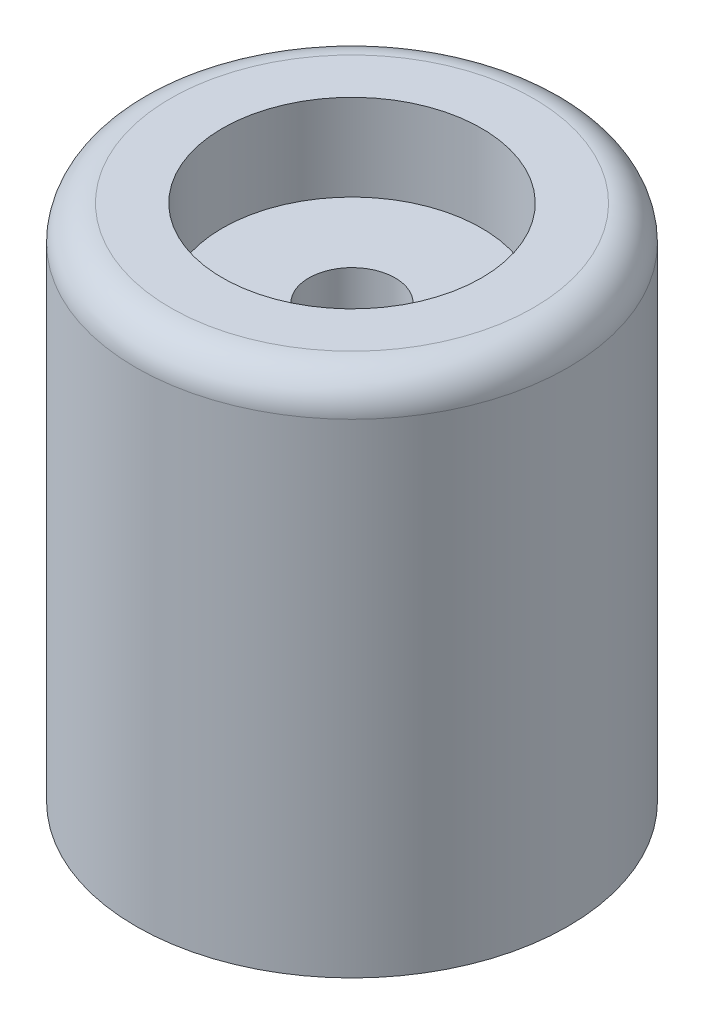
SolidWorks part; units mm, degrees
ref_plane "Front Plane" through (0, 0, 0) normal (0, 0, 1) x (1, 0, 0)
ref_plane "Top Plane" through (0, 0, 0) normal (0, 1, 0) x (1, 0, 0)
ref_plane "Right Plane" through (0, 0, 0) normal (1, 0, 0) x (0, 0, -1)
sketch "Sketch1" plane through (0, 0, 0) normal (0, 0, 1) x (1, 0, 0)
  line L0 (0, 0) -> (0, 134908.0691) construction
  line L1 (-3.175, 31.75) -> (-9.525, 31.75)
  line L2 (-9.525, 31.75) -> (-9.525, 38.1)
  line L3 (-9.525, 38.1) -> (-15.875, 38.1)
  line L4 (-15.875, 38.1) -> (-15.875, 0)
  line L5 (-15.875, 0) -> (-3.175, 0)
  line L6 (-3.175, 0) -> (-3.175, 31.75)
  dimension "D1" = 6.35
  dimension "D2" = 19.05
  dimension "D3" = 31.75
  dimension "D4" = 38.1
  dimension "D5" = 6.35
revolve "Revolve1" add sketch "Sketch1" angle 360 about L0
fillet "Fillet1" radius 2.54 1 edges at (15.875, 38.1, 0)
